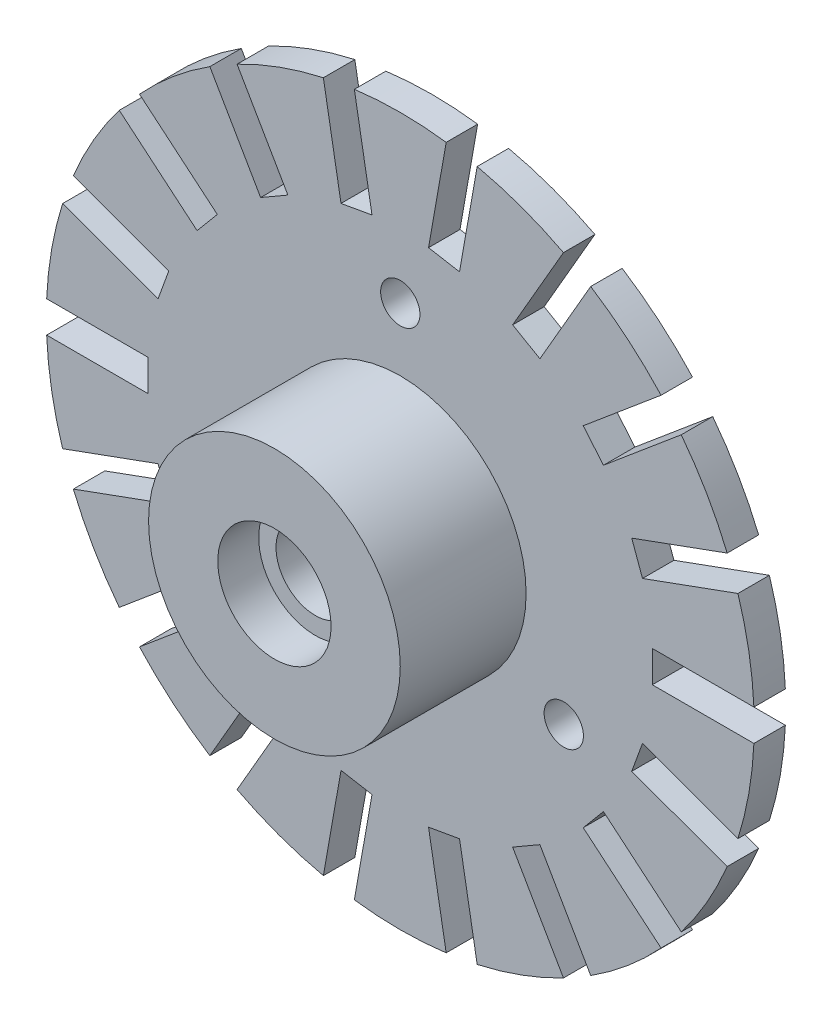
SolidWorks part; units mm, degrees
ref_plane "Front Plane" through (0, 0, 0) normal (0, 0, 1) x (1, 0, 0)
ref_plane "Top Plane" through (0, 0, 0) normal (0, 1, 0) x (1, 0, 0)
ref_plane "Right Plane" through (0, 0, 0) normal (1, 0, 0) x (0, 0, -1)
sketch "Sketch1" plane through (0, 0, 0) normal (0, 0, 1) x (1, 0, 0)
  circle A0 centre (0, 0) radius 22.5
  dimension "D1" = 45
extrude "Boss-Extrude1" add sketch "Sketch1" along normal blind 2
sketch "Sketch2" plane through (0, 0, 2) normal (0, 0, 1) x (1, 0, 0)
  circle A0 centre (0, 0) radius 8
extrude "Boss-Extrude2" add sketch "Sketch2" along normal blind 8
sketch "Sketch3" plane through (0, 0, 10) normal (0, 0, 1) x (1, 0, 0)
  circle A0 centre (0, 0) radius 2.5
extrude "Cut-Extrude1" cut sketch "Sketch3" against normal through all
sketch "Sketch4" plane through (0, 0, 10) normal (0, 0, 1) x (1, 0, 0)
  circle A0 centre (0, 0) radius 3.6
extrude "Cut-Extrude2" cut sketch "Sketch4" against normal blind 2.6
sketch "Sketch5" plane through (0, 0, 2) normal (0, 0, 1) x (1, 0, 0)
  line L0 (0, 12) -> (0, 0) construction
  line L1 (0, 0) -> (-10.3923, -6) construction
  line L2 (0, 0) -> (10.3923, -6) construction
  circle A0 centre (0, 12) radius 1.25
  circle A1 centre (-10.3923, -6) radius 1.25
  circle A2 centre (10.3923, -6) radius 1.25
  dimension "D1" = 120
  dimension "D3" = 2.5
  dimension "D4" = 2.5
  dimension "D5" = 2.5
  dimension "D2" = 120
  dimension "D6" = 12
  dimension "D7" = 12
  dimension "D8" = 12
extrude "Cut-Extrude3" cut sketch "Sketch5" against normal through all
sketch "Sketch7" plane through (0, 0, 2) normal (0, 0, 1) x (1, 0, 0)
  line L0 (15.8716, 0) -> (27.8716, 0) construction
  line L1 (16.0204, -1) -> (23.2374, -1)
  line L2 (16.0204, -1) -> (16.0204, 1)
  line L3 (16.0204, 1) -> (23.2374, 1)
  line L4 (23.2374, -1) -> (23.2374, 1)
  line L5 (16.0204, -1) -> (23.2374, 1) construction
  line L6 (16.0204, 1) -> (23.2374, -1) construction
  point P0 (19.6289, 0)
  dimension "D1" = 2
extrude "Cut-Extrude4" cut sketch "Sketch7" against normal blind 10
pattern_circular "CirPattern1" count 18 over 360 about axis through (0, 0, 0) along (0, 0, 1) of "Cut-Extrude4"
sketch "Sketch9" plane through (0, 0, -7) normal (0, 0, 1) x (1, 0, 0)
  circle A1 centre (10.3923, -6) radius 1.25
  circle A2 centre (-10.3923, -6) radius 1.25
  circle A3 centre (0, 12) radius 1.25
sketch "Sketch10" plane through (0, 0, 10) normal (0, 0, 1) x (1, 0, 0)
  line L0 (-8, 0) -> (8, 0) construction
  line L1 (0, 8) -> (0, -8) construction
  circle A0 centre (0, 0) radius 8 construction
